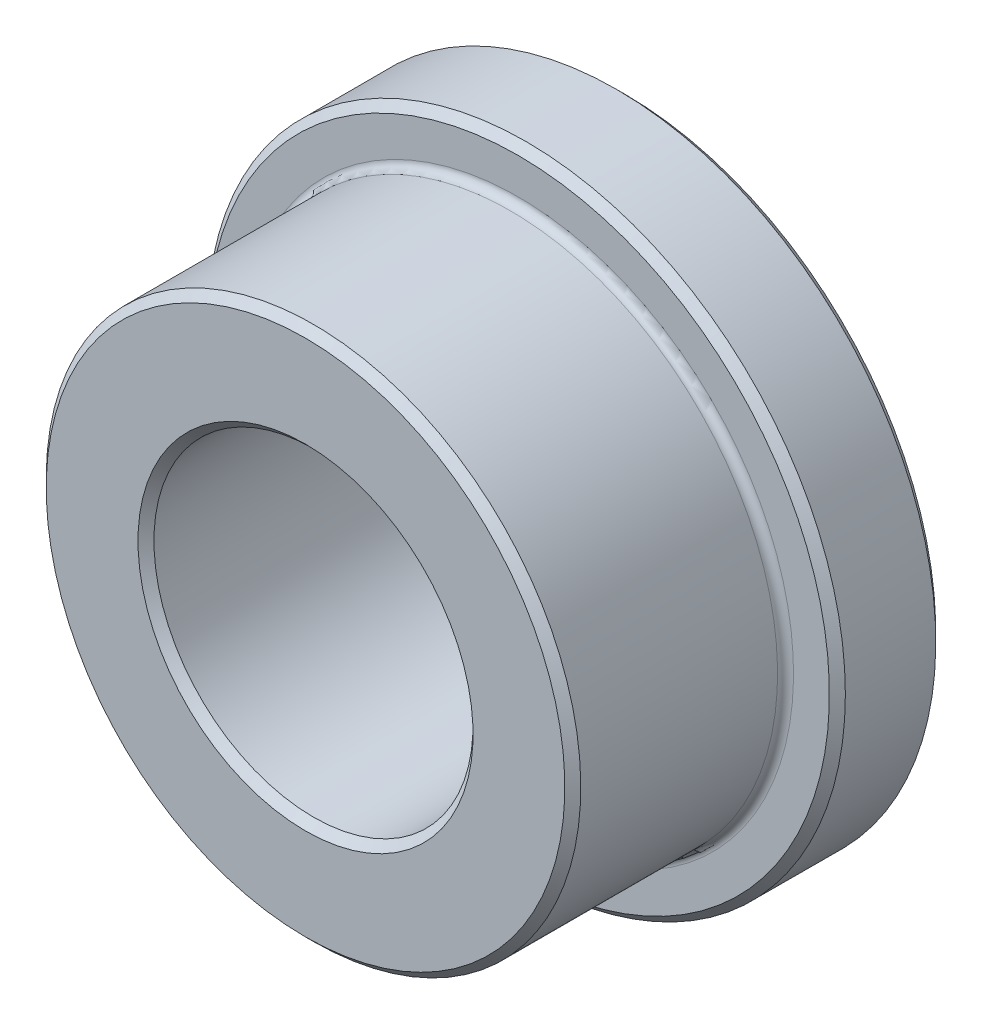
SolidWorks part; units mm, degrees
ref_plane "Front Plane" through (0, 0, 0) normal (0, 0, 1) x (1, 0, 0)
ref_plane "Top Plane" through (0, 0, 0) normal (0, 1, 0) x (1, 0, 0)
ref_plane "Right Plane" through (0, 0, 0) normal (1, 0, 0) x (0, 0, -1)
sketch "Sketch1" plane through (0, 0, 0) normal (0, 0, 1) x (1, 0, 0)
  circle A0 centre (0, 0) radius 3
  circle A1 centre (0, 0) radius 5.0255
  circle A2 centre (0, 0) radius 6
  point P5 (0, 5.0255)
  point P6 (0, 3)
  point P7 (0, 6)
  dimension "ID" = 6
  dimension "OD" = 10.051
  dimension "Flange OD" = 12
sketch "Sketch2" plane through (0, 0, 0) normal (1, 0, 0) x (0, 0, -1)
  line L0 (3, 0) -> (-3, 0)
  line L1 (3, 0) -> (3, 6)
  line L2 (3, 6) -> (1, 6)
  line L3 (1, 6) -> (1, 5.0255)
  line L4 (1, 5.0255) -> (-3, 5.0255)
  line L5 (-3, 5.0255) -> (-3, 3)
  line L6 (-3, 3) -> (3, 3)
  point P4 (0, 0)
  dimension "Flange Thickness" = 2
  dimension "Length" = 6
sketch "Sketch3" plane through (0, 0, 0) normal (1, 0, 0) x (0, 0, -1)
  line L0 (3, 6) -> (1, 6) construction
  line L1 (1, 6) -> (1, 5.0255) construction
  line L2 (1, 5.0255) -> (-3, 5.0255) construction
  line L3 (-3, 3) -> (3, 3) construction
  line L4 (-3, 5.0255) -> (-3, 3) construction
  line L5 (3, 6) -> (1, 6)
  line L6 (1, 6) -> (1, 5.0255)
  line L7 (1, 5.0255) -> (-3, 5.0255)
  line L8 (-3, 3) -> (3, 3)
  line L9 (-3, 5.0255) -> (-3, 3)
  line L10 (3, 6) -> (3, 3)
revolve "Revolve1" add sketch "Sketch3" angle 360 about L0
chamfer "Chamfer1" distance 0.15 angle 45 4 edges at (0, 6, -3) (0, 6, -1) (0, 5.0255, 3) (0, 3, 3)
fillet "Fillet1" radius 0.15 1 edges at (0, 5.0255, -1)
equation "\"D1@Chamfer1\"=\"Flange Thickness@Sketch2\"*.075"
equation "\"D1@Fillet1\"=\"D1@Chamfer1\""
